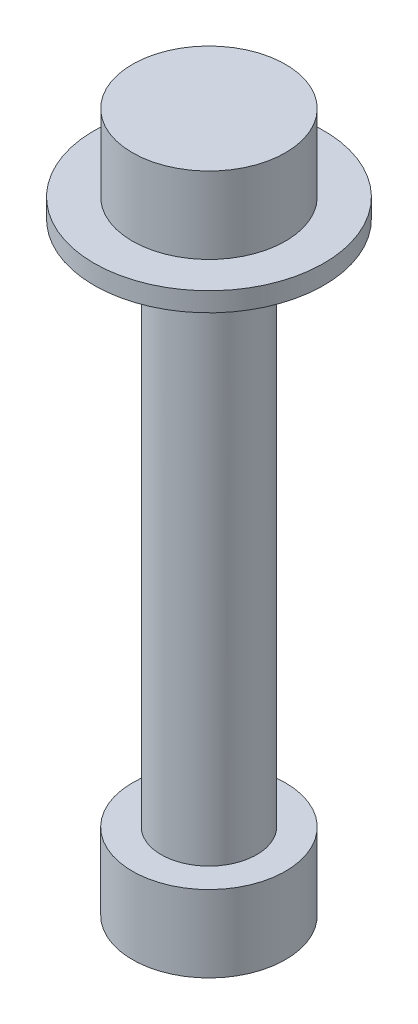
SolidWorks part; units mm, degrees
ref_plane "Front Plane" through (0, 0, 0) normal (0, 0, 1) x (1, 0, 0)
ref_plane "Top Plane" through (0, 0, 0) normal (0, 1, 0) x (1, 0, 0)
ref_plane "Right Plane" through (0, 0, 0) normal (1, 0, 0) x (0, 0, -1)
sketch "Sketch1" plane through (0, 0, 0) normal (0, 1, 0) x (1, 0, 0)
  circle A0 centre (0, 0) radius 3.175
  dimension "D1" = 6.35
extrude "Boss-Extrude1" add sketch "Sketch1" along normal blind 34.925
sketch "Sketch2" plane through (0, 34.925, 0) normal (0, 1, 0) x (1, 0, 0)
  circle A0 centre (0, 0) radius 7.62
  dimension "D1" = 15.24
extrude "Boss-Extrude2" add sketch "Sketch2" along normal blind 1.27
sketch "Sketch3" plane through (0, 0, 0) normal (0, -1, 0) x (1, 0, 0)
  circle A0 centre (0, 0) radius 5.08
  dimension "D1" = 10.16
extrude "Boss-Extrude3" add sketch "Sketch3" along normal blind 5.08
sketch "Sketch4" plane through (0, 36.195, 0) normal (0, 1, 0) x (1, 0, 0)
  circle A0 centre (0, 0) radius 5.08
  dimension "D1" = 10.16
extrude "Boss-Extrude4" add sketch "Sketch4" along normal blind 5.08
